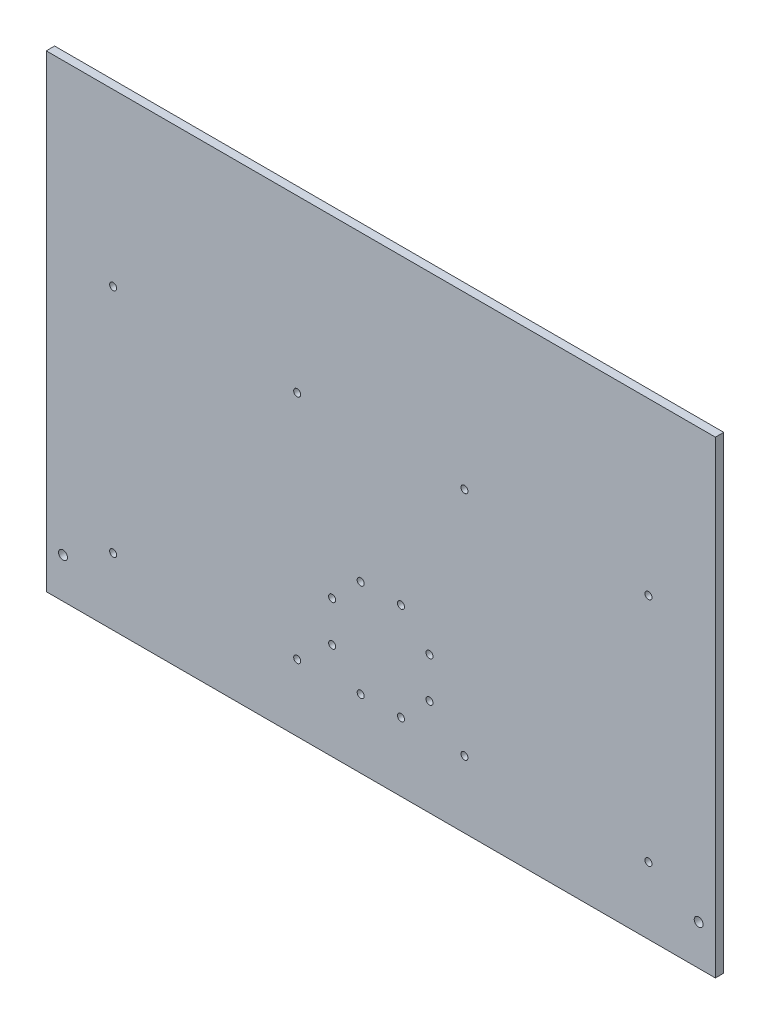
SolidWorks part; units mm, degrees
ref_plane "Plano frontal" through (0, 0, 0) normal (0, 0, 1) x (1, 0, 0)
ref_plane "Plano superior" through (0, 0, 0) normal (0, 1, 0) x (1, 0, 0)
ref_plane "Plano direito" through (0, 0, 0) normal (1, 0, 0) x (0, 0, -1)
sketch "Esboço1" plane through (0, 0, 0) normal (0, 0, 1) x (1, 0, 0)
  line L1 (-200, 140) -> (200, 140)
  line L2 (-200, 140) -> (-200, -140)
  line L3 (-200, -140) -> (200, -140)
  line L4 (200, 140) -> (200, -140)
  line L5 (-200, 140) -> (200, -140) construction
  line L6 (-200, -140) -> (200, 140) construction
  point P0 (0, 0)
  dimension "D1" = 400
  dimension "D2" = 280
extrude "Ressalto-extrusão1" add sketch "Esboço1" along normal blind 5
sketch "Esboço3" plane through (0, 0, 5) normal (0, 0, 1) x (1, 0, 0)
  line L0 (0, 140) -> (0, -140) construction
  line L1 (200, 140) -> (-200, 140) construction
  line L2 (-200, -140) -> (200, -140) construction
  line L3 (-200, -120) -> (200, -120) construction
  line L4 (-200, 140) -> (-200, -140) construction
  line L5 (200, -140) -> (200, 140) construction
  circle A0 centre (0, -70) radius 31.5 construction
  circle A1 centre (0, -70) radius 50 construction
  circle A2 centre (0, -38.5) radius 2.5 construction
  circle A3 centre (12.0545, -40.8978) radius 2.5 construction
  circle A4 centre (22.2739, -47.7261) radius 2.5 construction
  circle A5 centre (29.1022, -57.9455) radius 2.5 construction
  circle A6 centre (31.5, -70) radius 2.5 construction
  circle A7 centre (29.1022, -82.0545) radius 2.5 construction
  circle A8 centre (22.2739, -92.2739) radius 2.5 construction
  circle A9 centre (12.0545, -99.1022) radius 2.5 construction
  circle A10 centre (0, -101.5) radius 2.5 construction
  circle A11 centre (-12.0545, -99.1022) radius 2.5 construction
  circle A12 centre (-22.2739, -92.2739) radius 2.5 construction
  circle A13 centre (-29.1022, -82.0545) radius 2.5 construction
  circle A14 centre (-31.5, -70) radius 2.5 construction
  circle A15 centre (-29.1022, -57.9455) radius 2.5 construction
  circle A16 centre (-22.2739, -47.7261) radius 2.5 construction
  circle A17 centre (-12.0545, -40.8978) radius 2.5 construction
  point P51 (0, -70)
  dimension "D2" = 63
  dimension "D3" = 100
  dimension "D4" = 70
  dimension "D5" = 5
  dimension "D1" = 20
  dimension "D6" = 16
hole_wizard "Furo de diâmetro Ø4.2 (4.2)2" positions "3DSketch1" profile "Esboço4" hole size "Ø4.2" standard "DIN" end condition through all
sketch3d "3DSketch1"
  point P0 (12.0545, -40.8978, 5)
  point P3 (29.1022, -57.9455, 5)
  point P6 (29.1022, -82.0545, 5)
  point P9 (12.0545, -99.1022, 5)
  point P12 (-12.0545, -99.1022, 5)
  point P15 (-29.1022, -82.0545, 5)
  point P18 (-29.1022, -57.9455, 5)
  point P21 (-12.0545, -40.8978, 5)
sketch "Esboço4" plane through (12.0545, -40.8978, 5) normal (1, 0, 0) x (0, -1, 0)
  line L0 (0, 0) -> (0, 5)
  line L1 (0, 5) -> (2.1, 5)
  line L2 (2.1, 5) -> (2.1, 0)
  line L5 (2.1, 0) -> (0, 0)
  line L11 (0, -6.35) -> (0, 107.95) construction
  dimension "Thru Hole Dia." = 4.2
  dimension "Thru Hole Depth" = 5
sketch "Esboço5" plane through (0, 0, 5) normal (0, 0, 1) x (1, 0, 0)
  line L1 (-200, 140) -> (-200, -140) construction
  line L2 (200, -140) -> (200, 140) construction
  line L3 (-200, -140) -> (200, -140) construction
  line L4 (-190, 140) -> (-190, -140) construction
  line L5 (200, 140) -> (-200, 140) construction
  line L6 (190, 140) -> (190, -140) construction
  point P14 (-190, -116)
  point P15 (190, -116)
  dimension "D1" = 24
  dimension "D2" = 10
  dimension "D3" = 10
  dimension "D4" = 24
hole_wizard "Furo de diâmetro Ø5.3 (5.3)1" positions "3DSketch2" profile "Esboço6" hole size "Ø5.3" standard "DIN" end condition through all
sketch3d "3DSketch2"
  point P0 (-190, -116, 5)
  point P3 (190, -116, 5)
sketch "Esboço6" plane through (-190, -116, 5) normal (1, 0, 0) x (0, -1, 0)
  line L0 (0, 0) -> (0, 5)
  line L1 (0, 5) -> (2.65, 5)
  line L2 (2.65, 5) -> (2.65, 0)
  line L5 (2.65, 0) -> (0, 0)
  line L11 (0, -6.35) -> (0, 107.95) construction
  dimension "Thru Hole Dia." = 5.3
  dimension "Thru Hole Depth" = 5
sketch "Esboço7" plane through (0, 0, 5) normal (0, 0, 1) x (1, 0, 0)
  line L0 (-200, -100) -> (200, -100) construction
  line L1 (-200, 140) -> (-200, -140) construction
  line L2 (200, -140) -> (200, 140) construction
  line L3 (-200, 38) -> (200, 38) construction
  line L5 (-160, 140) -> (-160, -140) construction
  line L6 (200, 140) -> (-200, 140) construction
  line L7 (-200, -140) -> (200, -140) construction
  line L8 (-50, 140) -> (-50, -140) construction
  line L9 (50, 140) -> (50, -140) construction
  line L10 (160, 140) -> (160, -140) construction
  circle A0 centre (0, -70) radius 50 construction
  point P24 (-160, -100)
  point P25 (-50, -100)
  point P26 (-50, 38)
  point P27 (-160, 38)
  point P28 (50, 38)
  point P29 (50, -100)
  point P30 (160, -100)
  point P31 (160, 38)
  dimension "D1" = 40
  dimension "D2" = 138
  dimension "D3" = 40
  dimension "D4" = 40
hole_wizard "Furo de diâmetro Ø4.2 (4.2)1" positions "3DSketch3" profile "Esboço8" hole size "Ø4.2" standard "DIN" end condition through all
sketch3d "3DSketch3"
  point P0 (-160, 38, 5)
  point P3 (-50, 38, 5)
  point P6 (50, 38, 5)
  point P9 (160, 38, 5)
  point P12 (160, -100, 5)
  point P15 (50, -100, 5)
  point P18 (-50, -100, 5)
  point P21 (-160, -100, 5)
sketch "Esboço8" plane through (-160, 38, 5) normal (1, 0, 0) x (0, -1, 0)
  line L0 (0, 0) -> (0, 5)
  line L1 (0, 5) -> (2.1, 5)
  line L2 (2.1, 5) -> (2.1, 0)
  line L5 (2.1, 0) -> (0, 0)
  line L11 (0, -6.35) -> (0, 107.95) construction
  dimension "Thru Hole Dia." = 4.2
  dimension "Thru Hole Depth" = 5
